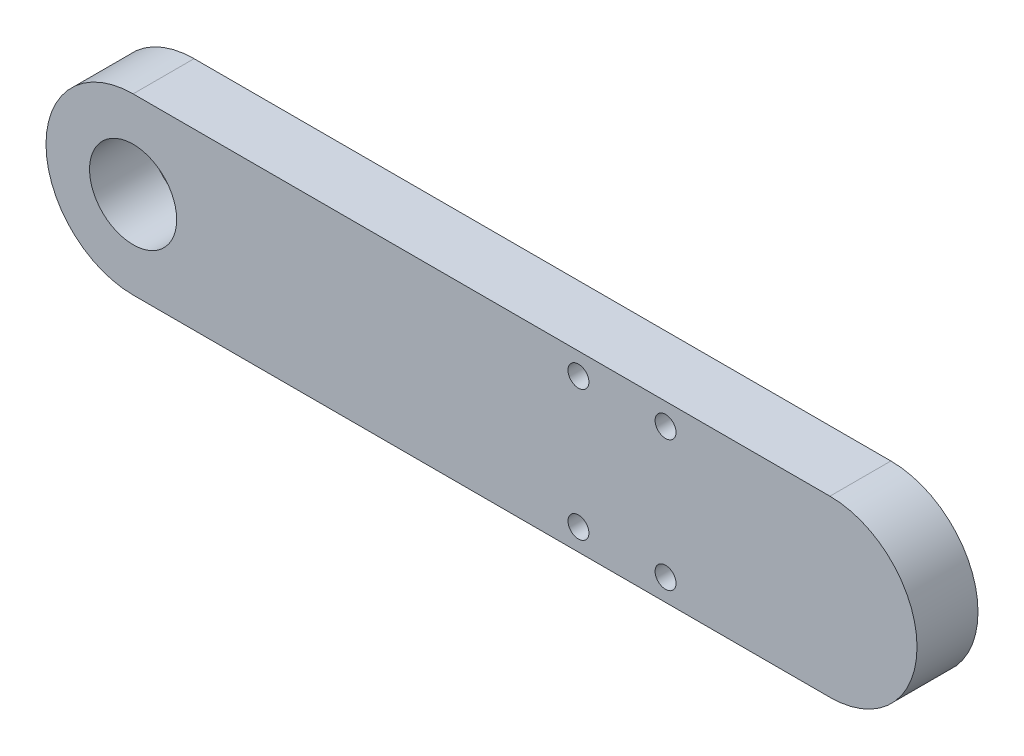
SolidWorks part; units mm, degrees
ref_plane "前视基准面" through (0, 0, 0) normal (0, 0, 1) x (1, 0, 0)
ref_plane "上视基准面" through (0, 0, 0) normal (0, 1, 0) x (1, 0, 0)
ref_plane "右视基准面" through (0, 0, 0) normal (1, 0, 0) x (0, 0, -1)
other "Configuration Table"
sketch "草图1" plane through (0, 0, 0) normal (0, 0, 1) x (1, 0, 0)
  line L0 (0, 10) -> (80, 10)
  line L1 (0, -10) -> (80, -10)
  circle A0 centre (0, 0) radius 10
  arc A1 (80, -10) -> (80, 10) centre (80, 0) ccw
  circle A2 centre (0, 0) radius 5
  dimension "D1" = 20
  dimension "D2" = 80
  dimension "D3" = 10
extrude "凸台-拉伸1" add sketch "草图1" along normal blind 7 contours A0 A2 | L1 A1 L0 A0
sketch "草图2" plane through (0, 0, 0) normal (0, 0, -1) x (-1, 0, 0)
  circle A0 centre (-51.129, -7.5) radius 1.2 construction
  circle A1 centre (-51.129, -7.5) radius 1.2
  circle A2 centre (-61.129, -7.5) radius 1.2 construction
  circle A3 centre (-61.129, -7.5) radius 1.2
  circle A4 centre (-61.129, 7.5) radius 1.2 construction
  circle A5 centre (-61.129, 7.5) radius 1.2
  circle A6 centre (-51.129, 7.5) radius 1.2 construction
  circle A7 centre (-51.129, 7.5) radius 1.2
extrude "切除-拉伸1" cut sketch "草图2" against normal blind 10
